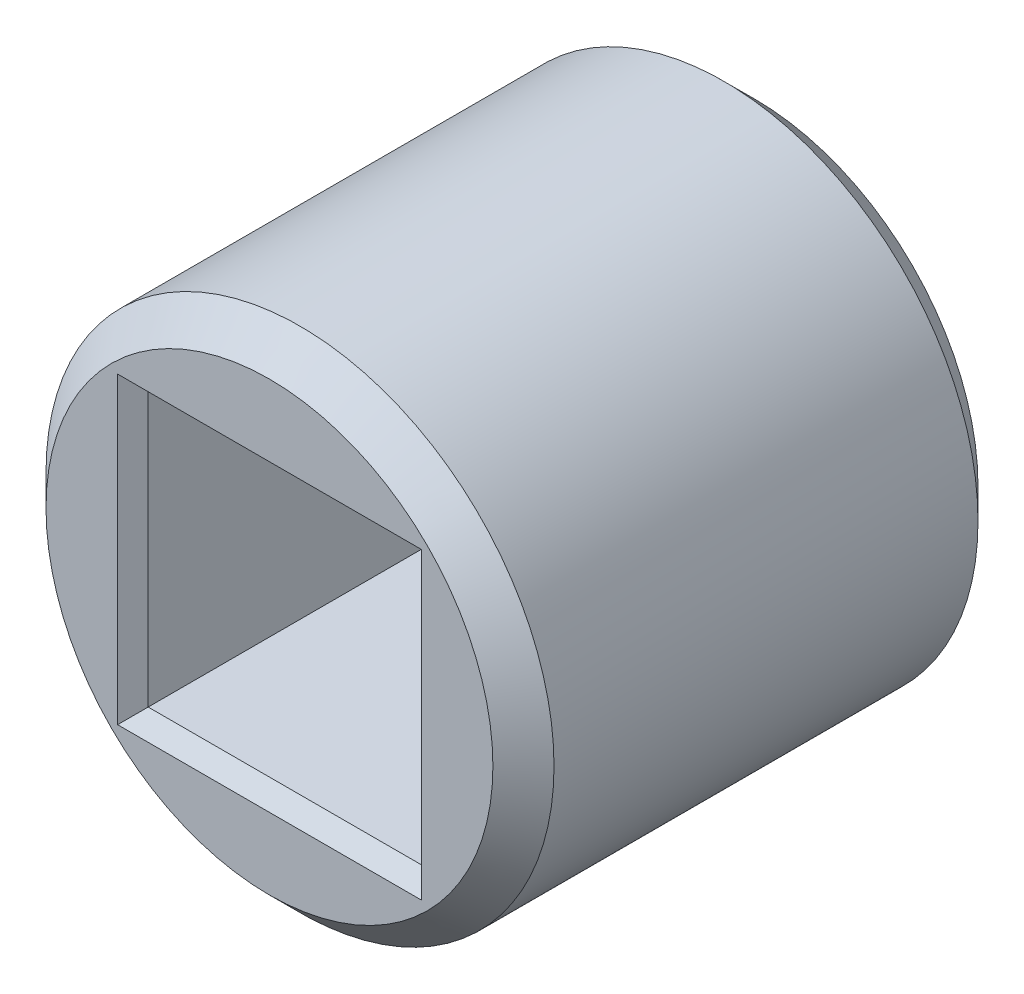
SolidWorks part; units mm, degrees
ref_plane "Front Plane" through (0, 0, 0) normal (0, 0, 1) x (1, 0, 0)
ref_plane "Top Plane" through (0, 0, 0) normal (0, 1, 0) x (1, 0, 0)
ref_plane "Right Plane" through (0, 0, 0) normal (1, 0, 0) x (0, 0, -1)
sketch "Sketch1" plane through (0, 0, 0) normal (0, 0, 1) x (1, 0, 0)
  line L1 (-1.7875, -1.7875) -> (1.7875, -1.7875)
  line L2 (-1.7875, -1.7875) -> (-1.7875, 1.7875)
  line L3 (-1.7875, 1.7875) -> (1.7875, 1.7875)
  line L4 (1.7875, -1.7875) -> (1.7875, 1.7875)
  line L5 (-1.7875, -1.7875) -> (1.7875, 1.7875) construction
  line L6 (-1.7875, 1.7875) -> (1.7875, -1.7875) construction
  circle A0 centre (0, 0) radius 3.325
  dimension "D1" = 6.65
  dimension "D2" = 3.575
  dimension "D3" = 3.575
extrude "Boss-Extrude1" add sketch "Sketch1" along normal blind 6.35
chamfer "Chamfer1" distance 0.4 angle 45 2 edges at (3.325, 0, 0) (3.325, 0, 6.35)
chamfer "Chamfer2" distance 0.2 angle 45 8 edges at (0, -1.7875, 0) (1.7875, 0, 0) (-1.7875, 0, 0) (0, 1.7875, 0) (1.7875, 0, 6.35) (0, 1.7875, 6.35) (-1.7875, 0, 6.35) (0, -1.7875, 6.35)
